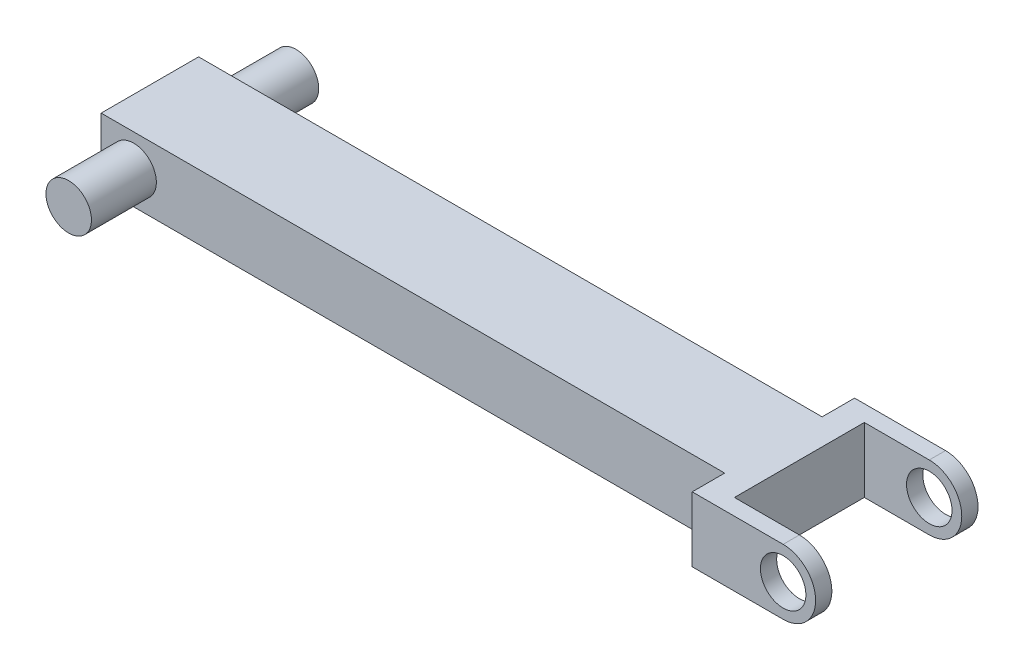
SolidWorks part; units mm, degrees
ref_plane "Front Plane" through (0, 0, 0) normal (0, 0, 1) x (1, 0, 0)
ref_plane "Top Plane" through (0, 0, 0) normal (0, 1, 0) x (1, 0, 0)
ref_plane "Right Plane" through (0, 0, 0) normal (1, 0, 0) x (0, 0, -1)
sketch "Sketch1" plane through (0, 0, 0) normal (0, 0, 1) x (1, 0, 0)
  line L1 (0, 0) -> (50.8, 0)
  line L2 (0, 0) -> (0, -5.08)
  line L3 (0, -5.08) -> (50.8, -5.08)
  line L4 (50.8, 0) -> (50.8, -5.08)
  dimension "D1" = 5.08
  dimension "D2" = 50.8
extrude "Boss-Extrude1" add sketch "Sketch1" along normal blind 7.62
sketch "Sketch2" plane through (0, 0, 7.62) normal (0, 0, 1) x (1, 0, 0)
  line L1 (0, 0) -> (0, -5.08) construction
  circle A0 centre (2.54, -2.54) radius 1.778
  point P8 (0, -2.54)
  dimension "D1" = 3.556
  dimension "D2" = 2.54
extrude "Boss-Extrude2" add sketch "Sketch2" along normal blind 5.08
sketch "Sketch3" plane through (0, 0, 0) normal (0, 0, -1) x (-1, 0, 0)
  circle A0 centre (-2.54, -2.54) radius 1.778
  dimension "D1" = 3.556
extrude "Boss-Extrude3" add sketch "Sketch3" along normal blind 5.08
sketch "Sketch4" plane through (0, 0, 7.62) normal (0, 0, 1) x (1, 0, 0)
  line L0 (0, -5.08) -> (50.8, -5.08) construction
  line L1 (50.8, 0) -> (48.768, 0)
  line L2 (50.8, 0) -> (50.8, -5.08)
  line L3 (50.8, -5.08) -> (48.768, -5.08)
  line L4 (48.768, 0) -> (48.768, -5.08)
  dimension "D1" = 2.032
extrude "Boss-Extrude4" add sketch "Sketch4" along normal blind 2.54
ref_plane "Plane1" through (0, 0, 10.16) normal (0, 0, 1) x (1, 0, 0)
sketch "Sketch5" plane through (0, 0, 10.16) normal (0, 0, 1) x (1, 0, 0)
  line L0 (48.768, -5.08) -> (50.8, -5.08) construction
  line L1 (50.8, 0) -> (55.88, 0)
  line L2 (50.8, 0) -> (50.8, -5.08)
  line L3 (50.8, -5.08) -> (55.88, -5.08)
  arc A0 (55.88, 0) -> (55.88, -5.08) centre (55.88, -2.54) cw
  dimension "D1" = 5.08
extrude "Boss-Extrude5" add sketch "Sketch5" against normal blind 1.27
sketch "Sketch6" plane through (0, 0, 0) normal (0, 0, -1) x (-1, 0, 0)
  line L0 (0, -5.08) -> (-50.8, -5.08) construction
  line L1 (-50.8, 0) -> (-48.768, 0)
  line L2 (-50.8, 0) -> (-50.8, -5.08)
  line L3 (-50.8, -5.08) -> (-48.768, -5.08)
  line L4 (-48.768, 0) -> (-48.768, -5.08)
extrude "Boss-Extrude6" add sketch "Sketch6" along normal blind 2.54
ref_plane "Plane2" through (0, 0, -2.54) normal (0, 0, -1) x (-1, 0, 0)
sketch "Sketch7" plane through (0, 0, -2.54) normal (0, 0, -1) x (-1, 0, 0)
  line L0 (-50.8, -5.08) -> (-48.768, -5.08) construction
  line L1 (-48.768, 0) -> (-55.88, 0)
  line L2 (-48.768, 0) -> (-48.768, -5.08)
  line L3 (-48.768, -5.08) -> (-55.88, -5.08)
  arc A0 (-55.88, -5.08) -> (-55.88, 0) centre (-55.88, -2.54) cw
extrude "Boss-Extrude7" add sketch "Sketch7" against normal blind 1.27
sketch "Sketch8" plane through (0, 0, -2.54) normal (0, 0, -1) x (-1, 0, 0)
  circle A0 centre (-55.88, -2.54) radius 1.778
extrude "Cut-Extrude1" cut sketch "Sketch8" against normal through all
ref_plane "Plane3" through (50.8, 0, -1.27) normal (1, 0, 0) x (0, 0, -1)
